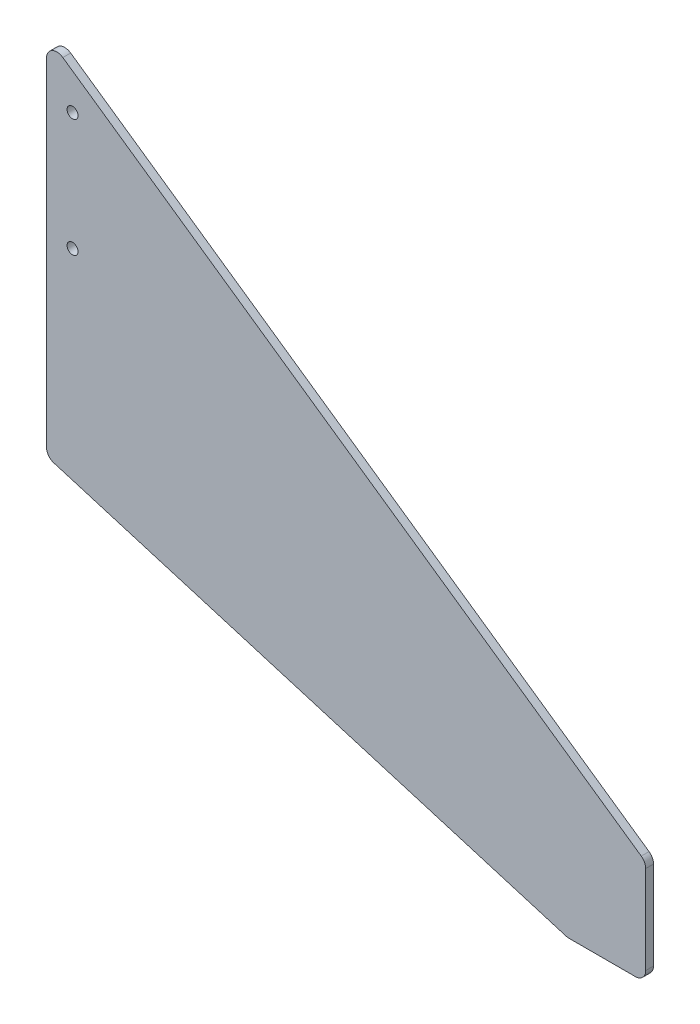
SolidWorks part; units mm, degrees
ref_plane "Спереди" through (0, 0, 0) normal (0, 0, 1) x (1, 0, 0)
ref_plane "Сверху" through (0, 0, 0) normal (0, 1, 0) x (1, 0, 0)
ref_plane "Справа" through (0, 0, 0) normal (1, 0, 0) x (0, 0, -1)
sketch "Эскиз1" plane through (0, 0, 0) normal (0, 0, 1) x (1, 0, 0)
  line L5 (0, 0) -> (0, 140)
  line L10 (0, 140) -> (230, -20)
  line L11 (230, -20) -> (230, -60)
  line L12 (230, -60) -> (200, -60)
  line L13 (200, -60) -> (0, 0)
  dimension "D1" = 230
  dimension "D2" = 40
  dimension "D3" = 30
  dimension "D4" = 140
  dimension "D5" = 60
extrude "Бобышка-Вытянуть1" add sketch "Эскиз1" along normal blind 3
sketch "Эскиз2" plane through (0, 0, 3) normal (0, 0, 1) x (1, 0, 0)
  line L0 (0, 140) -> (0, 0) construction
  circle A0 centre (10, 74) radius 2.1
  circle A1 centre (10, 119.2) radius 2.1
  dimension "D1" = 4.2
  dimension "D2" = 74
  dimension "D3" = 10
  dimension "D4" = 4.2
  dimension "D5" = 45.2
  dimension "D6" = 10
extrude "Вырез-Вытянуть1" cut sketch "Эскиз2" against normal blind 39
fillet "Скругление1" radius 4 5 edges at (200, -60, 1.5) (230, -60, 1.5) (230, -20, 1.5) (0, 0, 1.5) (0, 140, 1.5)
